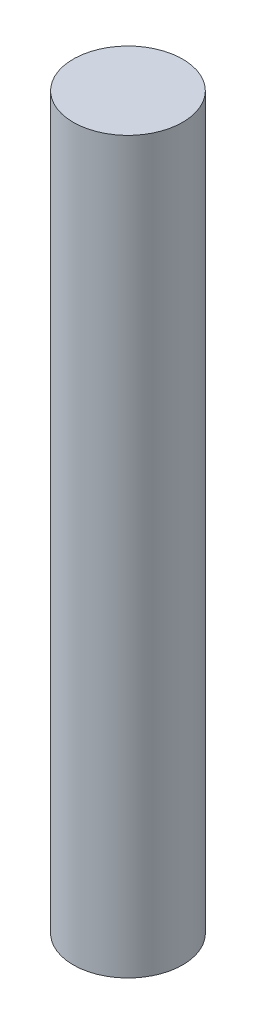
SolidWorks part; units mm, degrees
material "Rubber"
ref_plane "Front Plane" through (0, 0, 0) normal (0, 0, 1) x (1, 0, 0)
ref_plane "Top Plane" through (0, 0, 0) normal (0, 1, 0) x (1, 0, 0)
ref_plane "Right Plane" through (0, 0, 0) normal (1, 0, 0) x (0, 0, -1)
sketch "Sketch1" plane through (0, 0, 0) normal (0, 1, 0) x (1, 0, 0)
  circle A0 centre (0, 0) radius 1.5
extrude "Boss-Extrude1" add sketch "Sketch1" along normal blind 20
